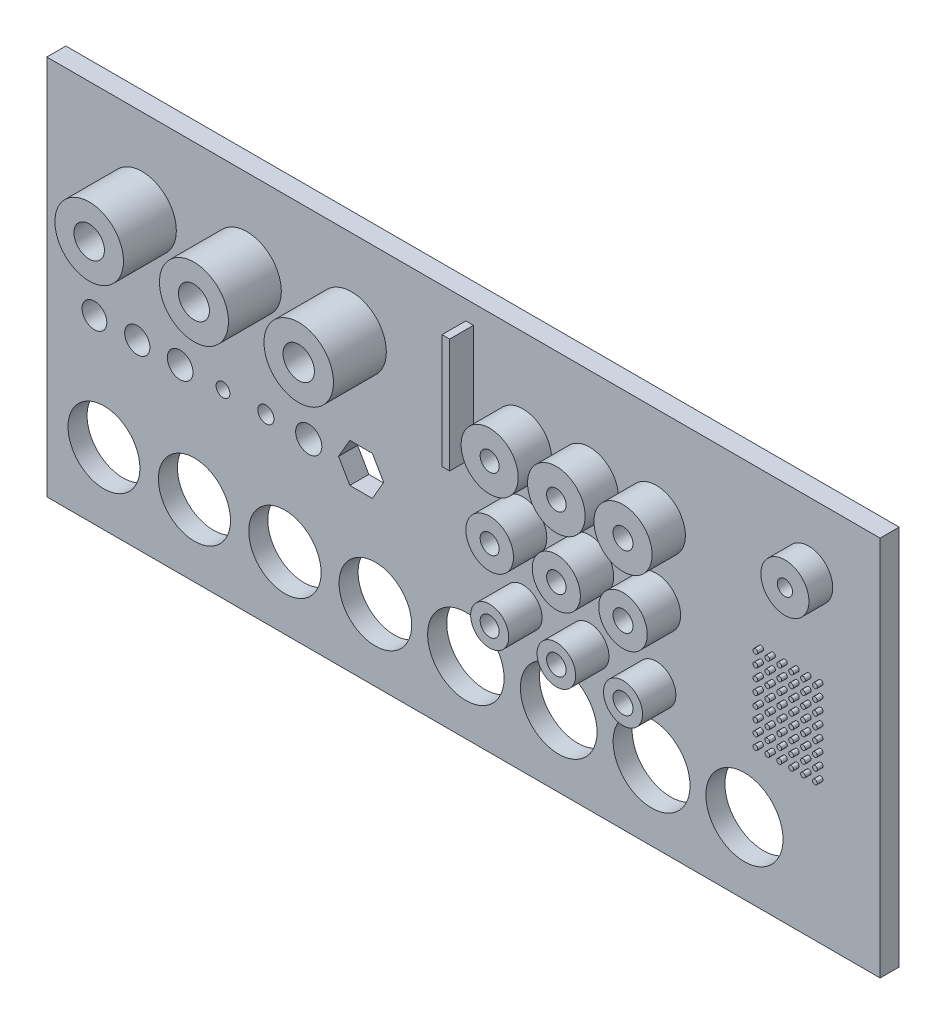
SolidWorks part; units mm, degrees
ref_plane "Front Plane" through (0, 0, 0) normal (0, 0, 1) x (1, 0, 0)
ref_plane "Top Plane" through (0, 0, 0) normal (0, 1, 0) x (1, 0, 0)
ref_plane "Right Plane" through (0, 0, 0) normal (1, 0, 0) x (0, 0, -1)
ref_plane "Plane1" through (0, 0, 300) normal (0, 0, 1) x (1, 0, 0)
sketch "Sketch1" plane through (0, 0, 300) normal (0, 0, 1) x (1, 0, 0)
  line L0 (300, 300) -> (475, 300)
  line L1 (475, 300) -> (475, 380)
  line L2 (475, 380) -> (300, 380)
  line L3 (300, 380) -> (300, 300)
  line L4 (370.7343, 338) -> (368.3671, 342.1)
  line L5 (368.3671, 342.1) -> (363.6329, 342.1)
  line L6 (363.6329, 342.1) -> (361.2657, 338)
  line L7 (361.2657, 338) -> (363.6329, 333.9)
  line L8 (363.6329, 333.9) -> (368.3671, 333.9)
  line L9 (368.3671, 333.9) -> (370.7343, 338)
  circle A0 centre (312, 315) radius 7.55
  circle A1 centre (331, 315) radius 7.575
  circle A2 centre (350, 315) radius 7.6
  circle A3 centre (369, 315) radius 7.625
  circle A4 centre (388, 315) radius 8.025
  circle A5 centre (407.5, 315) radius 8.05
  circle A6 centre (427, 315) radius 8.075
  circle A7 centre (446.5, 315) radius 8.1
  circle A8 centre (310, 338) radius 2.6
  circle A9 centre (319, 338) radius 2.65
  circle A10 centre (328, 338) radius 2.7
  circle A11 centre (337, 338) radius 1.45
  circle A12 centre (346, 338) radius 1.7
  circle A13 centre (355, 338) radius 2.75
extrude "Boss-Extrude1" add sketch "Sketch1" along normal blind 4
ref_plane "Plane2" through (0, 0, 304) normal (0, 0, 1) x (1, 0, 0)
sketch "Sketch2" plane through (0, 0, 304) normal (0, 0, 1) x (1, 0, 0)
  circle A0 centre (400, 330) radius 4
  circle A1 centre (400, 330) radius 2
extrude "Boss-Extrude2" add sketch "Sketch2" along normal blind 7
sketch "Sketch3" plane through (0, 0, 304) normal (0, 0, 1) x (1, 0, 0)
  circle A0 centre (400, 345) radius 5
  circle A1 centre (400, 345) radius 2
extrude "Boss-Extrude3" add sketch "Sketch3" along normal blind 7
sketch "Sketch4" plane through (0, 0, 304) normal (0, 0, 1) x (1, 0, 0)
  circle A0 centre (400, 360) radius 6
  circle A1 centre (400, 360) radius 2
extrude "Boss-Extrude4" add sketch "Sketch4" along normal blind 7
sketch "Sketch5" plane through (0, 0, 304) normal (0, 0, 1) x (1, 0, 0)
  circle A0 centre (414, 330) radius 4.05
  circle A1 centre (414, 330) radius 2.05
extrude "Boss-Extrude5" add sketch "Sketch5" along normal blind 7
sketch "Sketch6" plane through (0, 0, 304) normal (0, 0, 1) x (1, 0, 0)
  circle A0 centre (414, 345) radius 5.05
  circle A1 centre (414, 345) radius 2.05
extrude "Boss-Extrude6" add sketch "Sketch6" along normal blind 7
sketch "Sketch7" plane through (0, 0, 304) normal (0, 0, 1) x (1, 0, 0)
  circle A0 centre (414, 360) radius 6.05
  circle A1 centre (414, 360) radius 2.05
extrude "Boss-Extrude7" add sketch "Sketch7" along normal blind 7
sketch "Sketch8" plane through (0, 0, 304) normal (0, 0, 1) x (1, 0, 0)
  circle A0 centre (428, 330) radius 4.1
  circle A1 centre (428, 330) radius 2.1
extrude "Boss-Extrude8" add sketch "Sketch8" along normal blind 7
sketch "Sketch9" plane through (0, 0, 304) normal (0, 0, 1) x (1, 0, 0)
  circle A0 centre (428, 345) radius 5.1
  circle A1 centre (428, 345) radius 2.1
extrude "Boss-Extrude9" add sketch "Sketch9" along normal blind 7
sketch "Sketch10" plane through (0, 0, 304) normal (0, 0, 1) x (1, 0, 0)
  circle A0 centre (428, 360) radius 6.1
  circle A1 centre (428, 360) radius 2.1
extrude "Boss-Extrude10" add sketch "Sketch10" along normal blind 7
sketch "Sketch11" plane through (0, 0, 304) normal (0, 0, 1) x (1, 0, 0)
  circle A0 centre (320, 362) radius 7.2
  circle A1 centre (320, 362) radius 3.2
extrude "Boss-Extrude11" add sketch "Sketch11" along normal blind 11.1
sketch "Sketch12" plane through (0, 0, 304) normal (0, 0, 1) x (1, 0, 0)
  circle A0 centre (342, 362) radius 7.25
  circle A1 centre (342, 362) radius 3.25
extrude "Boss-Extrude12" add sketch "Sketch12" along normal blind 11.1
sketch "Sketch13" plane through (0, 0, 304) normal (0, 0, 1) x (1, 0, 0)
  circle A0 centre (364, 362) radius 7.3
  circle A1 centre (364, 362) radius 3.3
extrude "Boss-Extrude13" add sketch "Sketch13" along normal blind 11.1
sketch "Sketch14" plane through (0, 0, 304) normal (0, 0, 1) x (1, 0, 0)
  line L0 (388, 352) -> (389.6, 352)
  line L1 (389.6, 352) -> (389.6, 376)
  line L2 (389.6, 376) -> (388, 376)
  line L3 (388, 376) -> (388, 352)
extrude "Boss-Extrude14" add sketch "Sketch14" along normal blind 5
sketch "Sketch15" plane through (0, 0, 304) normal (0, 0, 1) x (1, 0, 0)
  circle A0 centre (450, 330) radius 0.5
  circle A1 centre (452.5, 330) radius 0.5
  circle A2 centre (455, 330) radius 0.5
  circle A3 centre (457.5, 330) radius 0.5
  circle A4 centre (460, 330) radius 0.5
  circle A5 centre (462.5, 330) radius 0.5
  circle A6 centre (450, 332.5) radius 0.5
  circle A7 centre (452.5, 332.5) radius 0.5
  circle A8 centre (455, 332.5) radius 0.5
  circle A9 centre (457.5, 332.5) radius 0.5
  circle A10 centre (460, 332.5) radius 0.5
  circle A11 centre (462.5, 332.5) radius 0.5
  circle A12 centre (450, 335) radius 0.5
  circle A13 centre (452.5, 335) radius 0.5
  circle A14 centre (455, 335) radius 0.5
  circle A15 centre (457.5, 335) radius 0.5
  circle A16 centre (460, 335) radius 0.5
  circle A17 centre (462.5, 335) radius 0.5
  circle A18 centre (450, 337.5) radius 0.5
  circle A19 centre (452.5, 337.5) radius 0.5
  circle A20 centre (455, 337.5) radius 0.5
  circle A21 centre (457.5, 337.5) radius 0.5
  circle A22 centre (460, 337.5) radius 0.5
  circle A23 centre (462.5, 337.5) radius 0.5
  circle A24 centre (450, 340) radius 0.5
  circle A25 centre (452.5, 340) radius 0.5
  circle A26 centre (455, 340) radius 0.5
  circle A27 centre (457.5, 340) radius 0.5
  circle A28 centre (460, 340) radius 0.5
  circle A29 centre (462.5, 340) radius 0.5
  circle A30 centre (450, 342.5) radius 0.5
  circle A31 centre (452.5, 342.5) radius 0.5
  circle A32 centre (455, 342.5) radius 0.5
  circle A33 centre (457.5, 342.5) radius 0.5
  circle A34 centre (460, 342.5) radius 0.5
  circle A35 centre (462.5, 342.5) radius 0.5
  circle A36 centre (450, 345) radius 0.5
  circle A37 centre (452.5, 345) radius 0.5
  circle A38 centre (455, 345) radius 0.5
  circle A39 centre (457.5, 345) radius 0.5
  circle A40 centre (460, 345) radius 0.5
  circle A41 centre (462.5, 345) radius 0.5
  circle A42 centre (450, 347.5) radius 0.5
  circle A43 centre (452.5, 347.5) radius 0.5
  circle A44 centre (455, 347.5) radius 0.5
  circle A45 centre (457.5, 347.5) radius 0.5
  circle A46 centre (460, 347.5) radius 0.5
  circle A47 centre (462.5, 347.5) radius 0.5
extrude "Boss-Extrude15" add sketch "Sketch15" along normal blind 1.2
sketch "Sketch16" plane through (0, 0, 300) normal (0, 0, 1) x (1, 0, 0)
  circle A0 centre (460, 366) radius 1.6
extrude "Cut-Extrude1" cut sketch "Sketch16" along normal blind 4
sketch "Sketch17" plane through (0, 0, 304) normal (0, 0, 1) x (1, 0, 0)
  circle A0 centre (460, 366) radius 5.05
  circle A1 centre (460, 366) radius 1.6
extrude "Boss-Extrude16" add sketch "Sketch17" along normal blind 5
